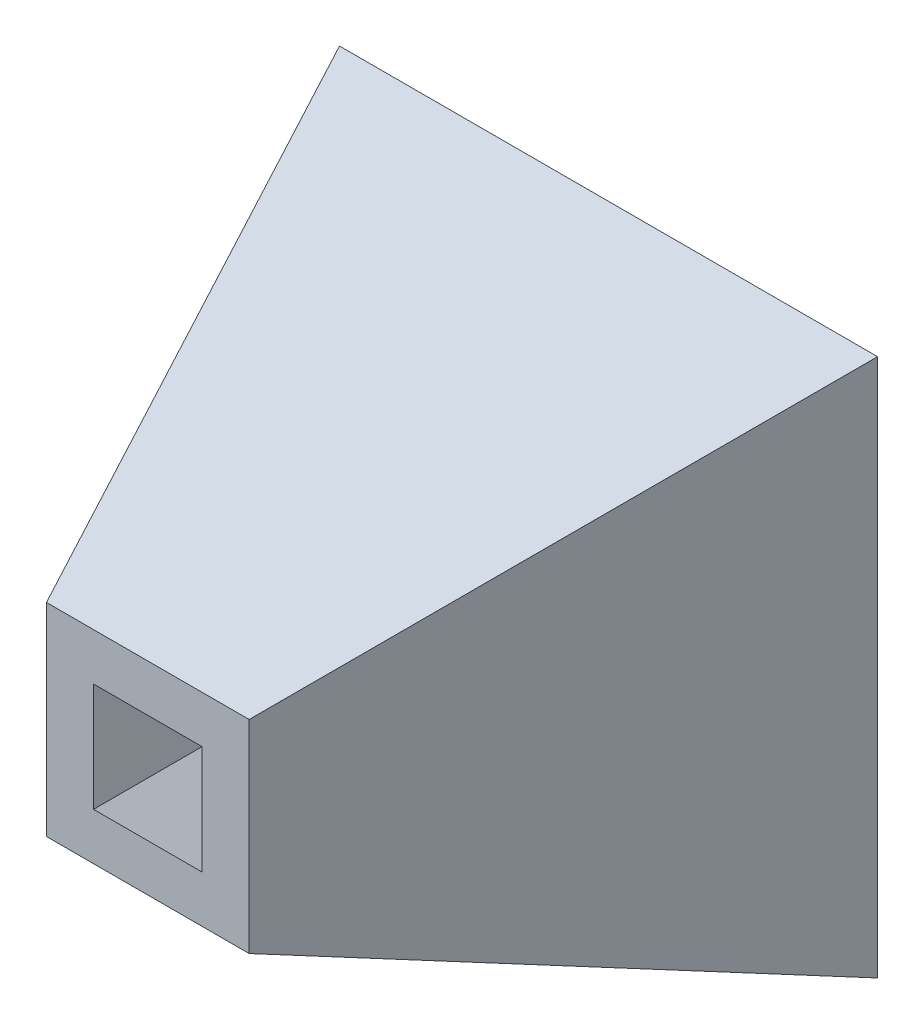
SolidWorks part; units mm, degrees
ref_plane "Front Plane" through (0, 0, 0) normal (0, 0, 1) x (1, 0, 0)
ref_plane "Top Plane" through (0, 0, 0) normal (0, 1, 0) x (1, 0, 0)
ref_plane "Right Plane" through (0, 0, 0) normal (1, 0, 0) x (0, 0, -1)
sketch "Sketch7" plane through (0, 0, 0) normal (0, 0, 1) x (1, 0, 0)
  line L0 (0, 0) -> (22, 0)
  line L1 (22, 0) -> (22, 22)
  line L2 (22, 22) -> (0, 22)
  line L3 (0, 22) -> (0, 0)
  dimension "D1" = 22
extrude "Boss-Extrude2" add sketch "Sketch7" along normal blind 50
draft "Draft2" type of draft neutral plane draft angle 20 faces to draft 4 face at (22, 11, 25) face at (11, 0, 25) face at (0, 11, 25) face at (11, 22, 25) neutral plane through (0, 0, 50) neutral plane normal (0, 0, 1) parameters "D1"=20
shell "Shell2" thickness 4.8
